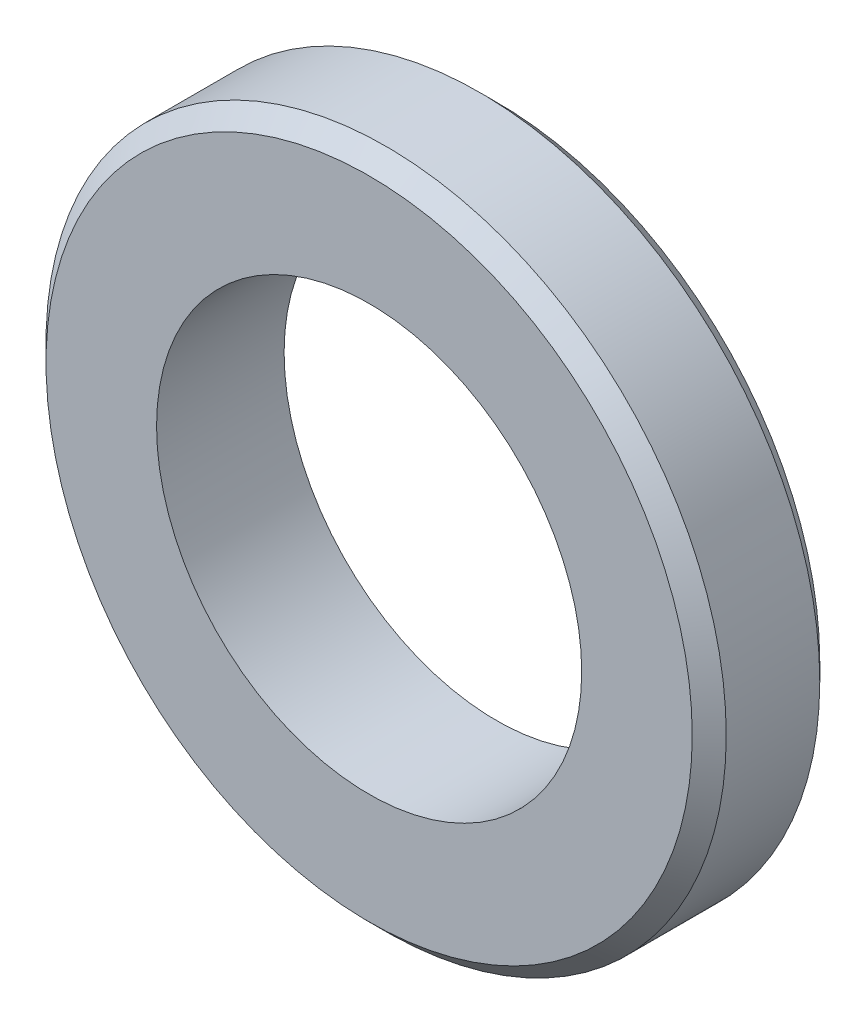
SolidWorks part; units mm, degrees
material "1023 Carbon Steel Sheet (SS)"
ref_plane "Front Plane" through (0, 0, 0) normal (0, 0, 1) x (1, 0, 0)
ref_plane "Top Plane" through (0, 0, 0) normal (0, 1, 0) x (1, 0, 0)
ref_plane "Right Plane" through (0, 0, 0) normal (1, 0, 0) x (0, 0, -1)
sketch "Sketch1" plane through (0, 0, 0) normal (0, 0, 1) x (1, 0, 0)
  circle A0 centre (0, 0) radius 5
  circle A1 centre (0, 0) radius 8
  dimension "D1" = 10
  dimension "D2" = 16
extrude "Boss-Extrude1" add sketch "Sketch1" along normal blind 3
chamfer "Chamfer1" distance 0.4 angle 45 2 edges at (8, 0, 0) (8, 0, 3)
